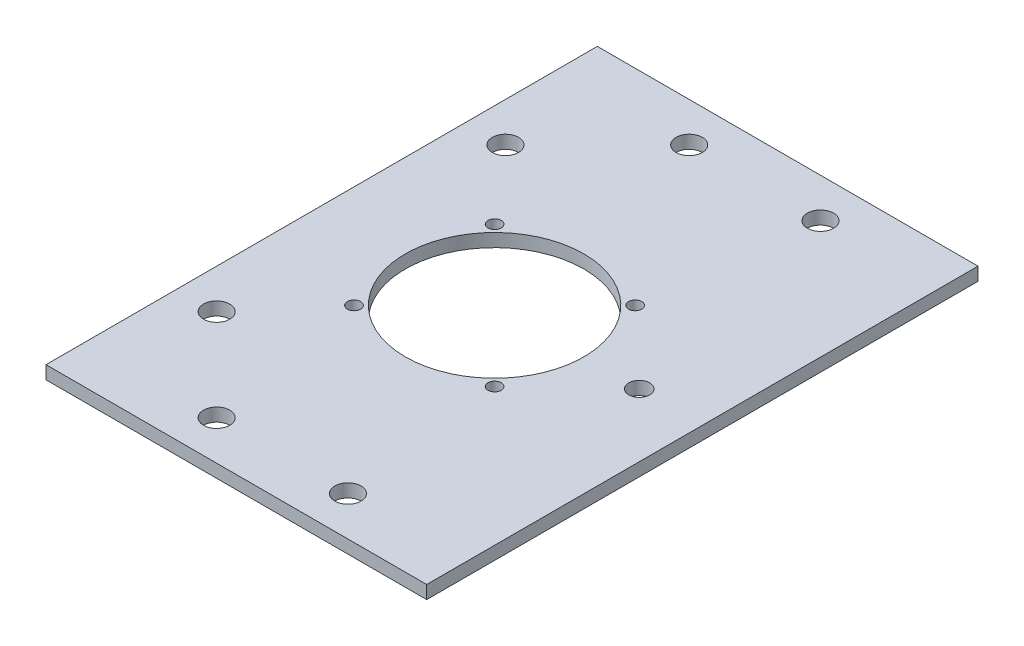
SolidWorks part; units mm, degrees
material "6061-T6 (SS)"
ref_plane "Front Plane" through (0, 0, 0) normal (0, 0, 1) x (1, 0, 0)
ref_plane "Top Plane" through (0, 0, 0) normal (0, 1, 0) x (1, 0, 0)
ref_plane "Right Plane" through (0, 0, 0) normal (1, 0, 0) x (0, 0, -1)
sketch "Sketch1" plane through (0, 0, 0) normal (0, 1, 0) x (1, 0, 0)
  line L1 (-95.25, -66.675) -> (95.25, -66.675)
  line L2 (-95.25, -66.675) -> (-95.25, 66.675)
  line L3 (-95.25, 66.675) -> (95.25, 66.675)
  line L4 (95.25, -66.675) -> (95.25, 66.675)
  line L5 (-95.25, -66.675) -> (95.25, 66.675) construction
  line L6 (-95.25, 66.675) -> (95.25, -66.675) construction
  point P0 (0, 0)
  dimension "D1" = 133.35
  dimension "D2" = 190.5
extrude "Boss-Extrude1" add sketch "Sketch1" along normal blind 3.175 contours L3 L4 L1 L2
sketch "Sketch3" plane through (0, 3.175, 0) normal (0, 1, 0) x (1, 0, 0)
  line L0 (-95.25, 0) -> (95.25, 0) construction
  line L1 (-95.25, -66.675) -> (-95.25, 66.675) construction
  line L2 (95.25, -66.675) -> (95.25, 66.675) construction
  circle A0 centre (-53.425, 0) radius 21.59
  dimension "D1" = 43.18
  dimension "D2" = 41.825
extrude "Cut-Extrude2" cut sketch "Sketch3" against normal through all
sketch "Sketch4" plane through (0, 3.175, 0) normal (0, 1, 0) x (1, 0, 0)
  line L0 (-70.425, 17) -> (-36.425, -17) construction
  line L5 (-53.425, 0) -> (22.4381, 0) construction
  line L6 (-70.425, 17) -> (-36.425, 17)
  line L7 (-53.425, 0) -> (-90.876, 0) construction
  line L8 (-70.425, 17) -> (-70.425, -17)
  line L9 (-70.425, -17) -> (-36.425, -17)
  line L10 (-36.425, 17) -> (-36.425, -17)
  line L11 (-36.425, 17) -> (-70.425, -17) construction
  line L12 (-36.425, 10.25) -> (-82.425, 10.25)
  circle A5 centre (-70.425, 17) radius 1.6
  circle A6 centre (-36.425, 17) radius 1.6
  circle A7 centre (-70.425, -17) radius 1.6
  circle A8 centre (-36.425, -17) radius 1.6
  circle A9 centre (-82.425, 10.25) radius 1.7
  circle A10 centre (-82.425, -10.25) radius 1.7
  circle A17 centre (-63.675, 29) radius 1.7
  circle A18 centre (-43.175, 29) radius 1.7
  circle A19 centre (-24.425, 10.25) radius 1.7
  circle A20 centre (-24.425, -10.25) radius 1.7
  circle A21 centre (-43.175, -29) radius 1.7
  circle A22 centre (-63.675, -29) radius 1.7
  point P10 (-53.425, 0)
  point P34 (-50.8425, 2.5825)
  point P47 (-53.425, 0)
  dimension "D8" = 3.4
  dimension "D10" = 4
  dimension "D1" = 3.2
  dimension "D5" = 6.75
  dimension "D7" = 3.4
  dimension "D2" = 34
  dimension "D3" = 34
  dimension "D4" = 0
  dimension "D6" = 12
extrude "Cut-Extrude3" cut sketch "Sketch4" against normal up to surface (3.175 mm away) up to face at (-53.425, 0, 21.59)
sketch "Sketch9" plane through (0, 3.175, 0) normal (0, 1, 0) x (1, 0, 0)
  line L4 (-95.25, 66.675) -> (-95.25, -66.675)
  line L20 (-95.25, 66.675) -> (-95.25, -66.675)
  line L24 (-95.25, -66.675) -> (95.25, -66.675)
  line L26 (-95.25, -66.675) -> (95.25, -66.675)
  line L28 (95.25, -66.675) -> (95.25, 66.675)
  line L29 (95.25, -66.675) -> (95.25, 66.675)
  line L30 (95.25, 66.675) -> (-95.25, 66.675)
  line L31 (95.25, 66.675) -> (-95.25, 66.675)
  circle A0 centre (-53.425, 0) radius 21.59 construction
  circle A1 centre (-53.425, 0) radius 21.59
  circle A6 centre (-18.4365, 0) radius 2.5273
  dimension "D2" = 34.9885
  dimension "D3" = 5.0546
  dimension "D1" = 0
extrude "Cut-Extrude5" cut sketch "Sketch9" against normal blind 10 contours A6
sketch "Sketch12" plane through (0, 3.175, 0) normal (0, 1, 0) x (1, 0, 0)
  line L0 (-95.25, 66.675) -> (95.25, 66.675) construction
  line L1 (-3.175, 66.675) -> (95.25, 66.675)
  line L2 (-3.175, 66.675) -> (-3.175, -66.675)
  line L3 (-3.175, -66.675) -> (95.25, -66.675)
  line L4 (95.25, 66.675) -> (95.25, -66.675)
  line L5 (-95.25, -66.675) -> (-95.25, 66.675) construction
  dimension "D1" = 92.075
extrude "Cut-Extrude6" cut sketch "Sketch12" against normal through all
sketch "Sketch13" plane through (0, 3.175, 0) normal (0, 1, 0) x (1, 0, 0)
  line L0 (-95.25, -66.675) -> (-3.175, -66.675) construction
  line L1 (-95.25, -66.675) -> (-95.25, 66.675) construction
  line L2 (-3.175, 66.675) -> (-3.175, -66.675) construction
  line L3 (-95.25, 0) -> (-3.175, 0) construction
  circle A0 centre (-63.5, -57.15) radius 3.175
  circle A1 centre (-31.75, -57.15) radius 3.175
  circle A2 centre (-85.725, -34.925) radius 3.175
  circle A3 centre (-85.725, 34.925) radius 3.175
  circle A4 centre (-31.75, 57.15) radius 3.175
  circle A5 centre (-63.5, 57.15) radius 3.175
  dimension "D1" = 6.35
  dimension "D4" = 6.35
  dimension "D6" = 6.35
  dimension "D2" = 9.525
  dimension "D3" = 31.75
  dimension "D5" = 31.75
  dimension "D7" = 31.75
  dimension "D8" = 9.525
  dimension "D9" = 0
extrude "Cut-Extrude7" cut sketch "Sketch13" against normal through all
